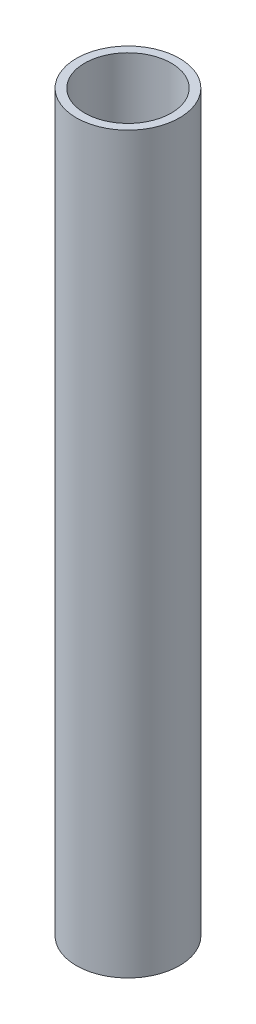
SolidWorks part; units mm, degrees
ref_plane "Alzado" through (0, 0, 0) normal (0, 0, 1) x (1, 0, 0)
ref_plane "Planta" through (0, 0, 0) normal (0, 1, 0) x (1, 0, 0)
ref_plane "Vista lateral" through (0, 0, 0) normal (1, 0, 0) x (0, 0, -1)
sketch "Croquis1" plane through (0, 0, 0) normal (0, 1, 0) x (1, 0, 0)
  circle A0 centre (0, 0) radius 12.5
  circle A1 centre (0, 0) radius 10.5
  dimension "D1" = 25
  dimension "D2" = 2
extrude "Saliente-Extruir1" add sketch "Croquis1" along normal blind 178
